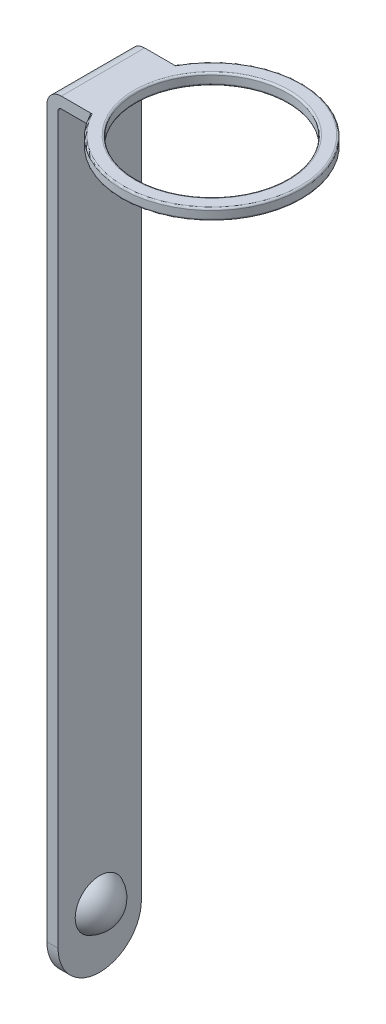
SolidWorks part; units mm, degrees
ref_plane "Plano frontal" through (0, 0, 0) normal (0, 0, 1) x (1, 0, 0)
ref_plane "Plano superior" through (0, 0, 0) normal (0, 1, 0) x (1, 0, 0)
ref_plane "Plano direito" through (0, 0, 0) normal (1, 0, 0) x (0, 0, -1)
sketch "Esboço1" plane through (0, 0, 0) normal (0, 0, 1) x (1, 0, 0)
  line L0 (0, 0) -> (0, -17.9385) construction
  line L2 (-4.92, 0) -> (-4.32, 0)
  line L3 (-5.02, -0.1) -> (-5.02, -0.52)
  line L4 (-4.92, -0.62) -> (-4.32, -0.62)
  line L5 (-4.22, -0.1) -> (-4.22, -0.52)
  arc A0 (-5.02, -0.52) -> (-4.92, -0.62) centre (-4.92, -0.52) ccw
  arc A1 (-4.92, 0) -> (-5.02, -0.1) centre (-4.92, -0.1) ccw
  arc A2 (-4.32, -0.62) -> (-4.22, -0.52) centre (-4.32, -0.52) ccw
  arc A3 (-4.32, 0) -> (-4.22, -0.1) centre (-4.32, -0.1) cw
  dimension "D4" = 0.1
  dimension "D1" = 8.44
  dimension "D2" = 10.04
  dimension "D3" = 0.62
revolve "Revolução1" add sketch "Esboço1" angle 360 about L0
sketch "Esboço2" plane through (0, 0, 0) normal (0, 0, 1) x (1, 0, 0)
  line L0 (-4.32, 0) -> (-6.06, 0)
  line L2 (-6.86, -0.8) -> (-6.86, -43.5)
  line L3 (5.02, -0.52) -> (5.02, -0.1) construction
  line L4 (-4.32, -0.62) -> (-6.06, -0.62)
  line L5 (-6.24, -0.8) -> (-6.24, -43.5)
  line L7 (-6.86, -43.5) -> (-6.24, -43.5)
  line L12 (-4.62, 0) -> (-6.06, 0) construction
  line L13 (-4.32, -0.1) -> (-4.32, -0.52)
  line L14 (-4.32, 0) -> (-4.32, -0.62)
  line L15 (-4.62, -0.62) -> (-6.06, -0.62) construction
  arc A0 (-6.06, 0) -> (-6.86, -0.8) centre (-6.06, -0.8) ccw
  arc A1 (-6.06, -0.62) -> (-6.24, -0.8) centre (-6.06, -0.8) ccw
  dimension "D2" = 0.8
  dimension "D1" = 11.88
  dimension "D4" = 43.5
  dimension "D5" = 0.1
extrude "Ressalto-extrusão1" add sketch "Esboço2" along normal mid plane 4.64
sketch "Esboço3" plane through (-6.86, 0, 0) normal (-1, 0, 0) x (0, 0, 1)
  line L0 (-2.32, -0.8) -> (-2.32, -43.5) construction
  line L1 (2.32, -0.8) -> (2.32, -43.5) construction
  line L2 (2.32, -43.5) -> (-2.32, -43.5) construction
  line L3 (-2.32, -41.18) -> (-5, -41.18)
  line L4 (-5, -41.18) -> (-5, -44.5)
  line L5 (-5, -44.5) -> (5, -44.5)
  line L6 (5, -44.5) -> (5, -41.18)
  line L7 (5, -41.18) -> (2.32, -41.18)
  arc A0 (-2.32, -41.18) -> (2.32, -41.18) centre (0, -41.18) ccw
  dimension "D1" = 5
  dimension "D2" = 5
  dimension "D3" = 1
extrude "Corte-extrusão1" cut sketch "Esboço3" against normal mid plane 4.64
sketch "Esboço4" plane through (0, 0, 0) normal (0, 0, 1) x (1, 0, 0)
  line L0 (-6.24, -40.2) -> (-4.875, -40.2) construction
  line L1 (-6.24, -41.18) -> (-6.24, -0.8) construction
  line L3 (-5.34, -40.0449) -> (-5.34, -40.5365) construction
  line L4 (-6.86, -41.18) -> (-6.86, -43.5) construction
  line L5 (-6.24, -40.2) -> (-5.34, -40.2)
  line L6 (-6.24, -40.2) -> (-6.46, -40.2)
  line L7 (-6.46, -40.2) -> (-6.46, -41.565)
  line L8 (-6.46, -41.565) -> (-6.24, -41.565)
  line L9 (-6.86, -0.8) -> (-6.86, -41.18) construction
  arc A0 (-6.24, -38.835) -> (-6.24, -41.565) centre (-6.24, -40.2) cw construction
  arc A1 (-5.34, -40.2) -> (-6.24, -41.565) centre (-6.8251, -40.2) cw
  dimension "D1" = 3.3
  dimension "D2" = 2.73
  dimension "D3" = 1.52
  dimension "D4" = 0.4
revolve "Revolução2" add sketch "Esboço4" angle 360 about L5
sketch "Esboço5" plane through (0, 0, 0) normal (0, 0, 1) x (1, 0, 0)
  line L0 (-6.5486, -41.1455) -> (-7.1788, -41.3298)
  line L1 (-5.84, -40.2) -> (-7.1769, -40.2)
  line L2 (-7.1769, -40.2) -> (-7.1788, -41.3298)
  arc A2 (-6.437, -41.1054) -> (-5.84, -40.2) centre (-6.8251, -40.2) ccw
  arc A3 (-6.5486, -41.1455) -> (-5.84, -40.2) centre (-6.8251, -40.2) ccw
  dimension "D2" = 16.3
  dimension "D1" = 0.5
revolve "Corte-Revolução1" cut sketch "Esboço5" angle 360 about L1
fillet "Filete1" radius 0.2 1 edges at (-6.86, -39.1634, 0)
sketch "Esboço7" plane through (-6.86, 0, 0) normal (-1, 0, 0) x (0, 0, 1)
  line L46 (1.0209, -19.8653) -> (0.7426, -19.7692)
  line L47 (-0.6335, -19.2924) -> (-0.9472, -19.184)
  line L48 (1.1473, -17.184) -> (1.1473, -16.8602)
  line L49 (1.1473, -16.8602) -> (-0.5736, -16.2645)
  line L50 (-0.5736, -16.2645) -> (1.0124, -16.3243)
  line L51 (1.0124, -16.3243) -> (1.0124, -15.9849)
  line L52 (1.0124, -15.9849) -> (-0.4834, -14.9465)
  line L53 (-0.4834, -14.9465) -> (1.1473, -15.5111)
  line L54 (1.1473, -15.5111) -> (1.1473, -15.1603)
  line L55 (1.1473, -15.1603) -> (-0.9843, -14.4221)
  line L56 (-0.9843, -14.4221) -> (-0.9843, -14.8492)
  line L57 (-0.9843, -14.8492) -> (0.5997, -15.9887)
  line L58 (0.5997, -15.9887) -> (-0.9843, -15.9731)
  line L59 (-0.9843, -15.9731) -> (-0.9843, -16.4457)
  line L60 (-0.9843, -16.4457) -> (1.1473, -17.184)
  line L61 (1.1473, -14.6476) -> (1.1473, -14.2699)
  line L62 (1.1473, -14.2699) -> (0.3109, -13.9802)
  line L63 (0.3109, -13.9802) -> (0.3109, -13.9048)
  line L64 (-0.9843, -13.3179) -> (-0.9843, -13.9094)
  line L65 (-0.9843, -13.9094) -> (1.1473, -14.6476)
  line L66 (1.1473, -13.2446) -> (1.1473, -12.9136)
  line L67 (1.1473, -12.9136) -> (0.5807, -12.4928)
  line L68 (0.5807, -12.4928) -> (0.5807, -11.6652)
  line L69 (0.5807, -11.6652) -> (1.1473, -11.6391)
  line L70 (1.1473, -11.6391) -> (1.1473, -11.2479)
  line L71 (1.1473, -11.2479) -> (-0.9843, -11.3271)
  line L72 (-0.9843, -11.3271) -> (-0.9843, -11.6787)
  line L73 (-0.9843, -11.6787) -> (1.1473, -13.2446)
  line L74 (1.0209, -9.2883) -> (0.7426, -9.1922)
  line L75 (-0.6335, -8.7153) -> (-0.9472, -8.607)
  line L76 (1.1473, -8.4147) -> (1.1473, -8.037)
  line L77 (1.1473, -8.037) -> (-0.7144, -7.3924)
  line L78 (-0.7144, -7.3924) -> (-0.7144, -6.6638)
  line L79 (-0.7144, -6.6638) -> (-0.9843, -6.5702)
  line L80 (-0.9843, -6.5702) -> (-0.9843, -8.405)
  line L81 (-0.9843, -8.405) -> (-0.7144, -8.4986)
  line L82 (-0.7144, -8.4986) -> (-0.7144, -7.7701)
  line L83 (-0.7144, -7.7701) -> (1.1473, -8.4147)
  line L84 (1.1473, -4.7451) -> (1.1473, -4.3674)
  line L85 (1.1473, -4.3674) -> (0.2569, -4.0592)
  line L86 (0.2569, -4.0592) -> (0.2569, -3.8459)
  line L87 (0.2569, -3.8459) -> (1.1473, -3.5811)
  line L88 (1.1473, -3.5811) -> (1.1473, -3.1532)
  line L89 (1.1473, -3.1532) -> (0.1452, -3.4765)
  line L90 (-0.9843, -3.3539) -> (-0.9843, -4.0069)
  line L91 (-0.9843, -4.0069) -> (1.1473, -4.7451)
  line L94 (-0.7144, -13.6253) -> (0.0411, -13.8866)
  line L95 (-0.7144, -13.5038) -> (-0.7144, -13.6253)
  line L99 (0.3109, -11.6644) -> (-0.5496, -11.6889)
  line L100 (-0.5496, -11.6889) -> (0.3109, -12.3057)
  line L101 (0.3109, -12.3057) -> (0.3109, -11.6644)
  line L104 (-0.7144, -3.7228) -> (-0.0129, -3.9656)
  line L105 (-0.7144, -3.5925) -> (-0.7144, -3.7228)
  line L107 (0.0411, -13.8866) -> (0.0411, -13.8251)
  line L109 (-0.0129, -3.9656) -> (-0.0129, -3.9247)
  spline S29 degree 3 poles (0.7426, -19.7692) (0.7576, -19.8064) (0.7867, -19.8784) (0.825, -19.9847) (0.8577, -20.0855) (0.8844, -20.1808) (0.9052, -20.2706) (0.9201, -20.3549) (0.9296, -20.4337) (0.9309, -20.4846) (0.9315, -20.5091) knots 0 0 0 0 0.156478 0.30356 0.441403 0.570199 0.690182 0.801102 0.904403 1 1 1 1
  spline S30 degree 3 poles (0.9315, -20.5091) (0.9309, -20.5336) (0.9297, -20.5808) (0.9197, -20.6487) (0.9024, -20.7104) (0.8784, -20.7659) (0.8472, -20.8151) (0.8094, -20.8582) (0.7642, -20.8949) (0.7126, -20.9253) (0.6544, -20.9484) (0.5905, -20.9641) (0.5207, -20.9713) (0.4455, -20.971) (0.3645, -20.9632) (0.2781, -20.9472) (0.1857, -20.924) (0.1233, -20.9032) (0.0908, -20.8923) knots 0 0 0 0 0.064742 0.124877 0.180885 0.233645 0.284273 0.334309 0.384756 0.43741 0.492281 0.549705 0.611028 0.677188 0.748495 0.825922 0.909488 1 1 1 1
  spline S31 degree 3 poles (0.0908, -20.8923) (0.0567, -20.8801) (-0.0102, -20.8561) (-0.1059, -20.8144) (-0.1956, -20.7704) (-0.2789, -20.7227) (-0.3557, -20.6716) (-0.4265, -20.6175) (-0.4913, -20.5604) (-0.5489, -20.4994) (-0.6006, -20.4367) (-0.6454, -20.3718) (-0.683, -20.3052) (-0.7147, -20.2375) (-0.7388, -20.1678) (-0.7554, -20.0964) (-0.7667, -20.0236) (-0.7678, -19.9744) (-0.7684, -19.9497) knots 0 0 0 0 0.07981 0.156238 0.229366 0.299568 0.367124 0.432164 0.495441 0.556879 0.616406 0.674196 0.729981 0.784472 0.838433 0.891815 0.945541 1 1 1 1
  spline S32 degree 3 poles (-0.7684, -19.9497) (-0.768, -19.9298) (-0.767, -19.888) (-0.7602, -19.822) (-0.7496, -19.7496) (-0.7346, -19.6706) (-0.7156, -19.5851) (-0.6923, -19.4932) (-0.6648, -19.3948) (-0.6442, -19.3273) (-0.6335, -19.2924) knots 0 0 0 0 0.08837 0.18653 0.295393 0.414553 0.544788 0.685609 0.837119 1 1 1 1
  spline S33 degree 3 poles (-0.9472, -19.184) (-0.9545, -19.2158) (-0.9689, -19.2781) (-0.9873, -19.3703) (-1.0031, -19.4593) (-1.0156, -19.5449) (-1.026, -19.6273) (-1.0331, -19.7064) (-1.0375, -19.7824) (-1.038, -19.8319) (-1.0382, -19.8561) knots 0 0 0 0 0.143722 0.28229 0.415179 0.542475 0.664354 0.781453 0.893286 1 1 1 1
  spline S34 degree 3 poles (-1.0382, -19.8561) (-1.0374, -19.897) (-1.0357, -19.978) (-1.0212, -20.0974) (-0.9988, -20.2133) (-0.9661, -20.325) (-0.9246, -20.4332) (-0.874, -20.5376) (-0.8136, -20.6379) (-0.7446, -20.7342) (-0.6675, -20.8257) (-0.5823, -20.9111) (-0.4899, -20.9905) (-0.3897, -21.0636) (-0.2827, -21.1312) (-0.1678, -21.1922) (-0.0459, -21.2479) (0.0394, -21.2788) (0.0828, -21.2945) knots 0 0 0 0 0.062771 0.124186 0.184172 0.243656 0.302542 0.361734 0.421288 0.482003 0.54319 0.604615 0.666829 0.729904 0.794612 0.860863 0.929259 1 1 1 1
  spline S35 degree 3 poles (0.0828, -21.2945) (0.1047, -21.302) (0.1476, -21.3167) (0.2116, -21.3355) (0.2738, -21.3516) (0.334, -21.365) (0.3923, -21.3765) (0.4488, -21.3835) (0.5033, -21.3897) (0.5561, -21.3912) (0.6069, -21.3919) (0.6558, -21.3879) (0.703, -21.3831) (0.7481, -21.3739) (0.7913, -21.3625) (0.8328, -21.3488) (0.8722, -21.3318) (0.9096, -21.312) (0.9451, -21.2897) (0.9782, -21.2646) (1.0091, -21.2371) (1.0378, -21.2072) (1.0641, -21.1744) (1.088, -21.1391) (1.1096, -21.1013) (1.129, -21.0612) (1.1464, -21.0184) (1.161, -20.973) (1.1731, -20.925) (1.1839, -20.8748) (1.1917, -20.8218) (1.1971, -20.7662) (1.2005, -20.7083) (1.201, -20.6688) (1.2013, -20.6487) knots 0 0 0 0 0.043009 0.084469 0.124181 0.162507 0.199236 0.234598 0.268508 0.301228 0.332875 0.363026 0.392516 0.421036 0.448632 0.475678 0.502157 0.528481 0.554458 0.580038 0.605603 0.631316 0.657172 0.683723 0.710551 0.738158 0.766668 0.796361 0.826874 0.858678 0.892005 0.926436 0.96259 1 1 1 1
  spline S36 degree 3 poles (1.2013, -20.6487) (1.2007, -20.6169) (1.1995, -20.5529) (1.1906, -20.4567) (1.1769, -20.3595) (1.1568, -20.2618) (1.1317, -20.1633) (1.1, -20.0644) (1.0637, -19.9645) (1.0352, -19.8986) (1.0209, -19.8653) knots 0 0 0 0 0.117722 0.236885 0.35786 0.481103 0.606371 0.734149 0.865593 1 1 1 1
  spline S37 degree 3 poles (1.2013, -18.6326) (1.2005, -18.5935) (1.1989, -18.5159) (1.1833, -18.4013) (1.1598, -18.2894) (1.125, -18.1807) (1.0817, -18.0745) (1.0283, -17.9712) (0.9646, -17.8712) (0.8923, -17.7745) (0.8121, -17.6827) (0.7254, -17.5965) (0.6331, -17.5166) (0.5343, -17.444) (0.4299, -17.3776) (0.3196, -17.3176) (0.2033, -17.2643) (0.1224, -17.2347) (0.0815, -17.2198) knots 0 0 0 0 0.060936 0.120784 0.179939 0.238957 0.298381 0.358527 0.419959 0.482862 0.546508 0.609851 0.67321 0.73664 0.800743 0.865821 0.932272 1 1 1 1
  spline S38 degree 3 poles (0.0815, -17.2198) (0.0611, -17.2129) (0.0207, -17.1994) (-0.0394, -17.1817) (-0.0982, -17.1669) (-0.1555, -17.1547) (-0.2113, -17.1449) (-0.2656, -17.1376) (-0.3185, -17.1335) (-0.3699, -17.1316) (-0.4198, -17.1329) (-0.4682, -17.1367) (-0.5153, -17.1429) (-0.5607, -17.1524) (-0.605, -17.1634) (-0.6473, -17.1785) (-0.6886, -17.1952) (-0.728, -17.215) (-0.7655, -17.2375) (-0.8011, -17.2616) (-0.8337, -17.289) (-0.8641, -17.3184) (-0.892, -17.3504) (-0.9179, -17.3843) (-0.9405, -17.4214) (-0.9614, -17.4602) (-0.9793, -17.5018) (-0.9956, -17.5454) (-1.0084, -17.5918) (-1.0195, -17.6401) (-1.0277, -17.6911) (-1.0342, -17.7443) (-1.0374, -17.8) (-1.038, -17.8379) (-1.0382, -17.8573) knots 0 0 0 0 0.04089 0.080543 0.118679 0.155676 0.191325 0.225943 0.259306 0.291783 0.323187 0.353878 0.383678 0.413003 0.44159 0.470029 0.497945 0.525906 0.553466 0.580624 0.607263 0.63398 0.660561 0.687539 0.714782 0.742515 0.770988 0.800447 0.830597 0.861966 0.894333 0.928357 0.963276 1 1 1 1
  spline S39 degree 3 poles (-1.0382, -17.8573) (-1.0374, -17.8947) (-1.0357, -17.9691) (-1.0209, -18.0795) (-0.9967, -18.1875) (-0.9636, -18.2934) (-0.9195, -18.3963) (-0.8672, -18.4974) (-0.8044, -18.5955) (-0.7329, -18.6909) (-0.6538, -18.7818) (-0.5676, -18.867) (-0.4753, -18.946) (-0.3761, -19.0181) (-0.2711, -19.0844) (-0.1597, -19.1444) (-0.042, -19.1983) (0.04, -19.2283) (0.0815, -19.2435) knots 0 0 0 0 0.059012 0.117354 0.175273 0.233389 0.292095 0.351581 0.412767 0.47563 0.539416 0.602739 0.666572 0.730814 0.796063 0.862314 0.930263 1 1 1 1
  spline S40 degree 3 poles (0.0815, -19.2435) (0.1024, -19.2505) (0.1435, -19.2642) (0.2046, -19.2825) (0.2643, -19.2976) (0.3223, -19.3105) (0.3789, -19.3199) (0.4337, -19.3278) (0.487, -19.3325) (0.5388, -19.3339) (0.5891, -19.3341) (0.6376, -19.3298) (0.6845, -19.3243) (0.7298, -19.3152) (0.7736, -19.3039) (0.816, -19.2901) (0.8566, -19.2729) (0.8957, -19.2538) (0.9327, -19.2318) (0.9676, -19.2078) (0.9996, -19.181) (1.0296, -19.1525) (1.0572, -19.1214) (1.0825, -19.0881) (1.1053, -19.0526) (1.1257, -19.0149) (1.1432, -18.9747) (1.159, -18.9326) (1.1719, -18.888) (1.1829, -18.8413) (1.1913, -18.7923) (1.1972, -18.7411) (1.2005, -18.6876) (1.201, -18.6511) (1.2013, -18.6326) knots 0 0 0 0 0.042196 0.082883 0.122032 0.160024 0.1966 0.231906 0.265932 0.299039 0.331053 0.362085 0.392183 0.421518 0.450423 0.478752 0.506731 0.534643 0.562141 0.589007 0.615564 0.642011 0.668306 0.694994 0.721858 0.749061 0.777005 0.805689 0.835142 0.865811 0.897478 0.930247 0.96448 1 1 1 1
  spline S41 degree 3 poles (0.3109, -13.9048) (0.3104, -13.87) (0.3093, -13.8017) (0.2999, -13.7011) (0.2843, -13.6044) (0.2628, -13.5112) (0.235, -13.4219) (0.2012, -13.3362) (0.1611, -13.2541) (0.1146, -13.1765) (0.0637, -13.1031) (0.0071, -13.036) (-0.0526, -12.974) (-0.1172, -12.9186) (-0.1858, -12.8687) (-0.259, -12.8252) (-0.3359, -12.7868) (-0.39, -12.7668) (-0.4172, -12.7568) knots 0 0 0 0 0.071615 0.140888 0.208118 0.27357 0.337922 0.400891 0.463496 0.525876 0.587466 0.647544 0.706572 0.764728 0.823049 0.881154 0.940259 1 1 1 1
  spline S42 degree 3 poles (-0.4172, -12.7568) (-0.436, -12.7506) (-0.4721, -12.7386) (-0.526, -12.726) (-0.5773, -12.7178) (-0.626, -12.7142) (-0.6722, -12.7159) (-0.7158, -12.7222) (-0.757, -12.7328) (-0.7825, -12.744) (-0.795, -12.7496) knots 0 0 0 0 0.15271 0.294618 0.427813 0.554258 0.671784 0.784974 0.894181 1 1 1 1
  spline S43 degree 3 poles (-0.795, -12.7496) (-0.8033, -12.7539) (-0.8198, -12.7624) (-0.842, -12.7793) (-0.863, -12.798) (-0.8824, -12.8193) (-0.8992, -12.8439) (-0.9149, -12.8704) (-0.9289, -12.8995) (-0.9406, -12.9317) (-0.9513, -12.9668) (-0.9599, -13.0057) (-0.9675, -13.0484) (-0.9738, -13.0948) (-0.9783, -13.1451) (-0.9816, -13.1993) (-0.9837, -13.2573) (-0.9841, -13.2973) (-0.9843, -13.3179) knots 0 0 0 0 0.044358 0.088423 0.132522 0.178514 0.225144 0.274069 0.325287 0.378895 0.436942 0.500134 0.568833 0.643175 0.723202 0.809752 0.901554 1 1 1 1
  spline S44 degree 3 poles (0.7426, -9.1922) (0.7576, -9.2293) (0.7867, -9.3014) (0.825, -9.4077) (0.8577, -9.5085) (0.8844, -9.6038) (0.9052, -9.6935) (0.9201, -9.7778) (0.9296, -9.8567) (0.9309, -9.9076) (0.9315, -9.9321) knots 0 0 0 0 0.156478 0.30356 0.441403 0.570199 0.690182 0.801102 0.904403 1 1 1 1
  spline S45 degree 3 poles (0.9315, -9.9321) (0.9309, -9.9565) (0.9297, -10.0038) (0.9197, -10.0716) (0.9024, -10.1333) (0.8784, -10.1888) (0.8472, -10.238) (0.8094, -10.2811) (0.7642, -10.3178) (0.7126, -10.3483) (0.6544, -10.3714) (0.5905, -10.3871) (0.5207, -10.3942) (0.4455, -10.394) (0.3645, -10.3862) (0.2781, -10.3701) (0.1857, -10.347) (0.1233, -10.3261) (0.0908, -10.3153) knots 0 0 0 0 0.064742 0.124877 0.180885 0.233645 0.284273 0.334309 0.384756 0.43741 0.492281 0.549705 0.611028 0.677188 0.748495 0.825922 0.909488 1 1 1 1
  spline S46 degree 3 poles (0.0908, -10.3153) (0.0567, -10.303) (-0.0102, -10.279) (-0.1059, -10.2374) (-0.1956, -10.1933) (-0.2789, -10.1456) (-0.3557, -10.0946) (-0.4265, -10.0404) (-0.4913, -9.9833) (-0.5489, -9.9224) (-0.6006, -9.8596) (-0.6454, -9.7947) (-0.683, -9.7281) (-0.7147, -9.6604) (-0.7388, -9.5907) (-0.7554, -9.5194) (-0.7667, -9.4466) (-0.7678, -9.3974) (-0.7684, -9.3726) knots 0 0 0 0 0.07981 0.156238 0.229366 0.299568 0.367124 0.432164 0.495441 0.556879 0.616406 0.674196 0.729981 0.784472 0.838433 0.891815 0.945541 1 1 1 1
  spline S47 degree 3 poles (-0.7684, -9.3726) (-0.768, -9.3528) (-0.767, -9.3109) (-0.7602, -9.2449) (-0.7496, -9.1725) (-0.7346, -9.0935) (-0.7156, -9.008) (-0.6923, -8.9161) (-0.6648, -8.8177) (-0.6442, -8.7503) (-0.6335, -8.7153) knots 0 0 0 0 0.08837 0.18653 0.295393 0.414553 0.544788 0.685609 0.837119 1 1 1 1
  spline S48 degree 3 poles (-0.9472, -8.607) (-0.9545, -8.6387) (-0.9689, -8.701) (-0.9873, -8.7933) (-1.0031, -8.8822) (-1.0156, -8.9679) (-1.026, -9.0502) (-1.0331, -9.1294) (-1.0375, -9.2053) (-1.038, -9.2548) (-1.0382, -9.279) knots 0 0 0 0 0.143722 0.28229 0.415179 0.542475 0.664354 0.781453 0.893286 1 1 1 1
  spline S49 degree 3 poles (-1.0382, -9.279) (-1.0374, -9.3199) (-1.0357, -9.4009) (-1.0212, -9.5203) (-0.9988, -9.6362) (-0.9661, -9.748) (-0.9246, -9.8562) (-0.874, -9.9605) (-0.8136, -10.0609) (-0.7446, -10.1571) (-0.6675, -10.2487) (-0.5823, -10.3341) (-0.4899, -10.4135) (-0.3897, -10.4865) (-0.2827, -10.5541) (-0.1678, -10.6152) (-0.0459, -10.6709) (0.0394, -10.7018) (0.0828, -10.7175) knots 0 0 0 0 0.062771 0.124186 0.184172 0.243656 0.302542 0.361734 0.421288 0.482003 0.54319 0.604615 0.666829 0.729904 0.794612 0.860863 0.929259 1 1 1 1
  spline S50 degree 3 poles (0.0828, -10.7175) (0.1047, -10.725) (0.1476, -10.7396) (0.2116, -10.7585) (0.2738, -10.7746) (0.334, -10.788) (0.3923, -10.7994) (0.4488, -10.8065) (0.5033, -10.8126) (0.5561, -10.8142) (0.6069, -10.8149) (0.6558, -10.8109) (0.703, -10.806) (0.7481, -10.7969) (0.7913, -10.7855) (0.8328, -10.7717) (0.8722, -10.7547) (0.9096, -10.7349) (0.9451, -10.7126) (0.9782, -10.6876) (1.0091, -10.6601) (1.0378, -10.6302) (1.0641, -10.5974) (1.088, -10.5621) (1.1096, -10.5243) (1.129, -10.4841) (1.1464, -10.4414) (1.161, -10.396) (1.1731, -10.348) (1.1839, -10.2977) (1.1917, -10.2448) (1.1971, -10.1892) (1.2005, -10.1312) (1.201, -10.0917) (1.2013, -10.0716) knots 0 0 0 0 0.043009 0.084469 0.124181 0.162507 0.199236 0.234598 0.268508 0.301228 0.332875 0.363026 0.392516 0.421036 0.448632 0.475678 0.502157 0.528481 0.554458 0.580038 0.605603 0.631316 0.657172 0.683723 0.710551 0.738158 0.766668 0.796361 0.826874 0.858678 0.892005 0.926436 0.96259 1 1 1 1
  spline S51 degree 3 poles (1.2013, -10.0716) (1.2007, -10.0398) (1.1995, -9.9759) (1.1906, -9.8796) (1.1769, -9.7825) (1.1568, -9.6847) (1.1317, -9.5863) (1.1, -9.4874) (1.0637, -9.3875) (1.0352, -9.3216) (1.0209, -9.2883) knots 0 0 0 0 0.117722 0.236885 0.35786 0.481103 0.606371 0.734149 0.865593 1 1 1 1
  spline S52 degree 3 poles (1.2013, -6.1937) (1.2005, -6.1546) (1.1989, -6.0771) (1.1833, -5.9625) (1.1598, -5.8506) (1.125, -5.7419) (1.0817, -5.6357) (1.0283, -5.5323) (0.9646, -5.4324) (0.8923, -5.3357) (0.8121, -5.2439) (0.7254, -5.1577) (0.6331, -5.0777) (0.5343, -5.0051) (0.4299, -4.9388) (0.3196, -4.8788) (0.2033, -4.8254) (0.1224, -4.7959) (0.0815, -4.781) knots 0 0 0 0 0.060936 0.120784 0.179939 0.238957 0.298381 0.358527 0.419959 0.482862 0.546508 0.609851 0.67321 0.73664 0.800743 0.865821 0.932272 1 1 1 1
  spline S53 degree 3 poles (0.0815, -4.781) (0.0611, -4.7741) (0.0207, -4.7606) (-0.0394, -4.7428) (-0.0982, -4.7281) (-0.1555, -4.7158) (-0.2113, -4.7061) (-0.2656, -4.6987) (-0.3185, -4.6946) (-0.3699, -4.6927) (-0.4198, -4.6941) (-0.4682, -4.6979) (-0.5153, -4.704) (-0.5607, -4.7136) (-0.605, -4.7246) (-0.6473, -4.7397) (-0.6886, -4.7564) (-0.728, -4.7762) (-0.7655, -4.7986) (-0.8011, -4.8228) (-0.8337, -4.8502) (-0.8641, -4.8796) (-0.892, -4.9115) (-0.9179, -4.9455) (-0.9405, -4.9825) (-0.9614, -5.0213) (-0.9793, -5.0629) (-0.9956, -5.1066) (-1.0084, -5.1529) (-1.0195, -5.2013) (-1.0277, -5.2523) (-1.0342, -5.3054) (-1.0374, -5.3612) (-1.038, -5.399) (-1.0382, -5.4184) knots 0 0 0 0 0.04089 0.080543 0.118679 0.155676 0.191325 0.225943 0.259306 0.291783 0.323187 0.353878 0.383678 0.413003 0.44159 0.470029 0.497945 0.525906 0.553466 0.580624 0.607263 0.63398 0.660561 0.687539 0.714782 0.742515 0.770988 0.800447 0.830597 0.861966 0.894333 0.928357 0.963276 1 1 1 1
  spline S54 degree 3 poles (-1.0382, -5.4184) (-1.0374, -5.4559) (-1.0357, -5.5303) (-1.0209, -5.6407) (-0.9967, -5.7486) (-0.9636, -5.8545) (-0.9195, -5.9574) (-0.8672, -6.0585) (-0.8044, -6.1567) (-0.7329, -6.252) (-0.6538, -6.343) (-0.5676, -6.4282) (-0.4753, -6.5072) (-0.3761, -6.5793) (-0.2711, -6.6456) (-0.1597, -6.7056) (-0.042, -6.7594) (0.04, -6.7894) (0.0815, -6.8046) knots 0 0 0 0 0.059012 0.117354 0.175273 0.233389 0.292095 0.351581 0.412767 0.47563 0.539416 0.602739 0.666572 0.730814 0.796063 0.862314 0.930263 1 1 1 1
  spline S55 degree 3 poles (0.0815, -6.8046) (0.1024, -6.8116) (0.1435, -6.8254) (0.2046, -6.8436) (0.2643, -6.8588) (0.3223, -6.8716) (0.3789, -6.8811) (0.4337, -6.889) (0.487, -6.8937) (0.5388, -6.895) (0.5891, -6.8952) (0.6376, -6.8909) (0.6845, -6.8854) (0.7298, -6.8763) (0.7736, -6.865) (0.816, -6.8512) (0.8566, -6.8341) (0.8957, -6.815) (0.9327, -6.793) (0.9676, -6.769) (0.9996, -6.7422) (1.0296, -6.7136) (1.0572, -6.6826) (1.0825, -6.6493) (1.1053, -6.6138) (1.1257, -6.5761) (1.1432, -6.5359) (1.159, -6.4937) (1.1719, -6.4491) (1.1829, -6.4025) (1.1913, -6.3534) (1.1972, -6.3022) (1.2005, -6.2487) (1.201, -6.2123) (1.2013, -6.1937) knots 0 0 0 0 0.042196 0.082883 0.122032 0.160024 0.1966 0.231906 0.265932 0.299039 0.331053 0.362085 0.392183 0.421518 0.450423 0.478752 0.506731 0.534643 0.562141 0.589007 0.615564 0.642011 0.668306 0.694994 0.721858 0.749061 0.777005 0.805689 0.835142 0.865811 0.897478 0.930247 0.96448 1 1 1 1
  spline S56 degree 3 poles (0.1452, -3.4765) (0.1316, -3.4426) (0.1045, -3.3746) (0.0495, -3.2789) (-0.0148, -3.1879) (-0.0769, -3.1177) (-0.1302, -3.0645) (-0.1721, -3.0278) (-0.2151, -2.9941) (-0.2591, -2.9631) (-0.3043, -2.9353) (-0.3506, -2.9103) (-0.3983, -2.8887) (-0.4309, -2.8767) (-0.4472, -2.8707) knots 0 0 0 0 0.12537 0.251099 0.377739 0.507315 0.572476 0.636062 0.698603 0.759906 0.820559 0.880782 0.940595 1 1 1 1
  spline S57 degree 3 poles (-0.4472, -2.8707) (-0.4676, -2.8641) (-0.5067, -2.8515) (-0.5649, -2.8397) (-0.6197, -2.8338) (-0.6712, -2.8348) (-0.7193, -2.843) (-0.7641, -2.8572) (-0.8054, -2.8785) (-0.8429, -2.9063) (-0.8766, -2.9405) (-0.9056, -2.9813) (-0.9301, -3.0284) (-0.9505, -3.0813) (-0.9651, -3.1409) (-0.9766, -3.2062) (-0.9833, -3.278) (-0.9839, -3.3279) (-0.9843, -3.3539) knots 0 0 0 0 0.071518 0.137101 0.197911 0.255148 0.308428 0.360192 0.411375 0.462686 0.515419 0.570868 0.629192 0.691993 0.759791 0.833583 0.913201 1 1 1 1
  spline S62 degree 3 poles (-0.7684, -17.9509) (-0.7678, -17.9732) (-0.7664, -18.0179) (-0.7561, -18.0844) (-0.7386, -18.1496) (-0.7142, -18.2138) (-0.6835, -18.2771) (-0.6457, -18.3392) (-0.601, -18.4002) (-0.5497, -18.4598) (-0.492, -18.5174) (-0.4285, -18.5725) (-0.3587, -18.6242) (-0.283, -18.6733) (-0.2011, -18.719) (-0.1136, -18.7623) (-0.0198, -18.8017) (0.0453, -18.8254) (0.0786, -18.8375) knots 0 0 0 0 0.051347 0.102573 0.153973 0.20603 0.259835 0.31526 0.37274 0.433122 0.495612 0.559632 0.62601 0.694806 0.766577 0.841007 0.918763 1 1 1 1
  spline S63 degree 3 poles (0.0786, -17.6233) (0.0461, -17.6125) (-0.0165, -17.5918) (-0.1087, -17.5678) (-0.1952, -17.5501) (-0.2763, -17.5396) (-0.3518, -17.537) (-0.4217, -17.541) (-0.4864, -17.5515) (-0.5453, -17.5701) (-0.5979, -17.5953) (-0.644, -17.6269) (-0.6829, -17.6653) (-0.7144, -17.7104) (-0.7391, -17.7616) (-0.756, -17.8193) (-0.7668, -17.883) (-0.7679, -17.9276) (-0.7684, -17.9509) knots 0 0 0 0 0.092566 0.178218 0.257686 0.331238 0.398938 0.461773 0.520391 0.575812 0.628175 0.677627 0.726278 0.775107 0.825771 0.879401 0.937206 1 1 1 1
  spline S64 degree 3 poles (0.9315, -18.5394) (0.9309, -18.5153) (0.9296, -18.4674) (0.9188, -18.3964) (0.9009, -18.3272) (0.8762, -18.2595) (0.8451, -18.1931) (0.8062, -18.1286) (0.7606, -18.0658) (0.7081, -18.0048) (0.6497, -17.9457) (0.5848, -17.8902) (0.5148, -17.8373) (0.4385, -17.788) (0.3568, -17.7416) (0.2692, -17.6988) (0.1763, -17.6584) (0.1116, -17.6351) (0.0786, -17.6233) knots 0 0 0 0 0.054002 0.107583 0.160682 0.214369 0.269122 0.325008 0.38306 0.443246 0.505481 0.569226 0.634778 0.702502 0.772854 0.845651 0.921246 1 1 1 1
  spline S65 degree 3 poles (0.0786, -18.8375) (0.1119, -18.8487) (0.1761, -18.8704) (0.2707, -18.8949) (0.3589, -18.9137) (0.4414, -18.9242) (0.5179, -18.9285) (0.5884, -18.9253) (0.6529, -18.9151) (0.7113, -18.8975) (0.7629, -18.8728) (0.8085, -18.8429) (0.8466, -18.8063) (0.8781, -18.7643) (0.9025, -18.7162) (0.919, -18.6623) (0.9299, -18.6028) (0.9309, -18.5611) (0.9315, -18.5394) knots 0 0 0 0 0.096205 0.185293 0.267357 0.342966 0.412664 0.476581 0.535825 0.590935 0.642888 0.691955 0.739287 0.786823 0.835155 0.885997 0.940692 1 1 1 1
  spline S68 degree 3 poles (-0.3957, -13.1691) (-0.4094, -13.1647) (-0.4357, -13.1563) (-0.4739, -13.1471) (-0.5094, -13.1428) (-0.5419, -13.1425) (-0.5713, -13.1467) (-0.5978, -13.1547) (-0.6213, -13.1674) (-0.6417, -13.1849) (-0.6591, -13.207) (-0.6744, -13.234) (-0.6868, -13.2663) (-0.6968, -13.3038) (-0.7046, -13.3464) (-0.7105, -13.3942) (-0.7137, -13.4473) (-0.7142, -13.4844) (-0.7144, -13.5038) knots 0 0 0 0 0.072879 0.139288 0.198735 0.253489 0.303066 0.348498 0.393047 0.436933 0.483465 0.535061 0.593162 0.658023 0.731103 0.81207 0.901847 1 1 1 1
  spline S69 degree 3 poles (0.0411, -13.8251) (0.0408, -13.8051) (0.0403, -13.766) (0.0345, -13.7084) (0.0257, -13.653) (0.0137, -13.5998) (-0.0025, -13.5491) (-0.0219, -13.5007) (-0.0451, -13.4548) (-0.0717, -13.4112) (-0.1016, -13.3703) (-0.1347, -13.3323) (-0.1705, -13.2969) (-0.2101, -13.2656) (-0.2518, -13.236) (-0.297, -13.2106) (-0.3451, -13.1879) (-0.3786, -13.1755) (-0.3957, -13.1691) knots 0 0 0 0 0.070734 0.138761 0.204823 0.269202 0.331878 0.393089 0.453881 0.514001 0.573856 0.633158 0.692313 0.751803 0.811889 0.873217 0.935365 1 1 1 1
  spline S74 degree 3 poles (0.0786, -5.1844) (0.0461, -5.1737) (-0.0165, -5.1529) (-0.1087, -5.1289) (-0.1952, -5.1113) (-0.2763, -5.1007) (-0.3518, -5.0982) (-0.4217, -5.1022) (-0.4864, -5.1127) (-0.5453, -5.1313) (-0.5979, -5.1565) (-0.644, -5.188) (-0.6829, -5.2264) (-0.7144, -5.2716) (-0.7391, -5.3228) (-0.756, -5.3805) (-0.7668, -5.4442) (-0.7679, -5.4888) (-0.7684, -5.512) knots 0 0 0 0 0.092566 0.178218 0.257686 0.331238 0.398938 0.461773 0.520391 0.575812 0.628175 0.677627 0.726278 0.775107 0.825771 0.879401 0.937206 1 1 1 1
  spline S75 degree 3 poles (0.9315, -6.1006) (0.9309, -6.0765) (0.9296, -6.0286) (0.9188, -5.9576) (0.9009, -5.8883) (0.8762, -5.8206) (0.8451, -5.7542) (0.8062, -5.6898) (0.7606, -5.627) (0.7081, -5.5659) (0.6497, -5.5069) (0.5848, -5.4514) (0.5148, -5.3984) (0.4385, -5.3492) (0.3568, -5.3028) (0.2692, -5.26) (0.1763, -5.2195) (0.1116, -5.1963) (0.0786, -5.1844) knots 0 0 0 0 0.054002 0.107583 0.160682 0.214369 0.269122 0.325008 0.38306 0.443246 0.505481 0.569226 0.634778 0.702502 0.772854 0.845651 0.921246 1 1 1 1
  spline S76 degree 3 poles (0.0786, -6.3986) (0.1119, -6.4099) (0.1761, -6.4315) (0.2707, -6.456) (0.3589, -6.4749) (0.4414, -6.4854) (0.5179, -6.4897) (0.5884, -6.4865) (0.6529, -6.4763) (0.7113, -6.4586) (0.7629, -6.434) (0.8085, -6.4041) (0.8466, -6.3675) (0.8781, -6.3254) (0.9025, -6.2774) (0.919, -6.2234) (0.9299, -6.164) (0.9309, -6.1223) (0.9315, -6.1006) knots 0 0 0 0 0.096205 0.185293 0.267357 0.342966 0.412664 0.476581 0.535825 0.590935 0.642888 0.691955 0.739287 0.786823 0.835155 0.885997 0.940692 1 1 1 1
  spline S77 degree 3 poles (-0.7684, -5.512) (-0.7678, -5.5344) (-0.7664, -5.5791) (-0.7561, -5.6456) (-0.7386, -5.7108) (-0.7142, -5.7749) (-0.6835, -5.8382) (-0.6457, -5.9004) (-0.601, -5.9614) (-0.5497, -6.021) (-0.492, -6.0785) (-0.4285, -6.1337) (-0.3587, -6.1854) (-0.283, -6.2345) (-0.2011, -6.2801) (-0.1136, -6.3234) (-0.0198, -6.3629) (0.0453, -6.3866) (0.0786, -6.3986) knots 0 0 0 0 0.051347 0.102573 0.153973 0.20603 0.259835 0.31526 0.37274 0.433122 0.495612 0.559632 0.62601 0.694806 0.766577 0.841007 0.918763 1 1 1 1
  spline S80 degree 3 poles (-0.4197, -3.2582) (-0.4316, -3.2545) (-0.4543, -3.2474) (-0.4879, -3.2403) (-0.5193, -3.238) (-0.5483, -3.2402) (-0.5753, -3.2457) (-0.5998, -3.2567) (-0.6218, -3.2716) (-0.6418, -3.2906) (-0.6588, -3.3141) (-0.6743, -3.3414) (-0.6866, -3.3731) (-0.6967, -3.409) (-0.7045, -3.4489) (-0.7105, -3.4931) (-0.7136, -3.5414) (-0.7142, -3.5751) (-0.7144, -3.5925) knots 0 0 0 0 0.067327 0.128577 0.184937 0.23675 0.285791 0.333088 0.380719 0.42909 0.481219 0.537018 0.5984 0.664786 0.738405 0.818147 0.905746 1 1 1 1
  spline S81 degree 3 poles (-0.0129, -3.9247) (-0.0133, -3.9033) (-0.0139, -3.8617) (-0.0186, -3.8006) (-0.0265, -3.7424) (-0.0377, -3.6871) (-0.0527, -3.635) (-0.0702, -3.5855) (-0.0914, -3.5391) (-0.1154, -3.4953) (-0.143, -3.4549) (-0.1732, -3.417) (-0.2073, -3.383) (-0.2437, -3.3514) (-0.2833, -3.3233) (-0.3259, -3.2982) (-0.3714, -3.2762) (-0.4035, -3.2642) (-0.4197, -3.2582) knots 0 0 0 0 0.076298 0.148765 0.218665 0.285781 0.34995 0.412327 0.472958 0.532028 0.590203 0.647646 0.704773 0.761703 0.819626 0.877887 0.938034 1 1 1 1
extrude "Ressalto-extrusão2" add sketch "Esboço7" along normal mid plane 0.2 separate body
combine bodies "Combinar1" operation type subtract main body 105 bodies to subtract 106 107 108 109 110 111 112 113 114
scale "Escala1" scale about centroid uniform scaling yes scale factor 0.85
